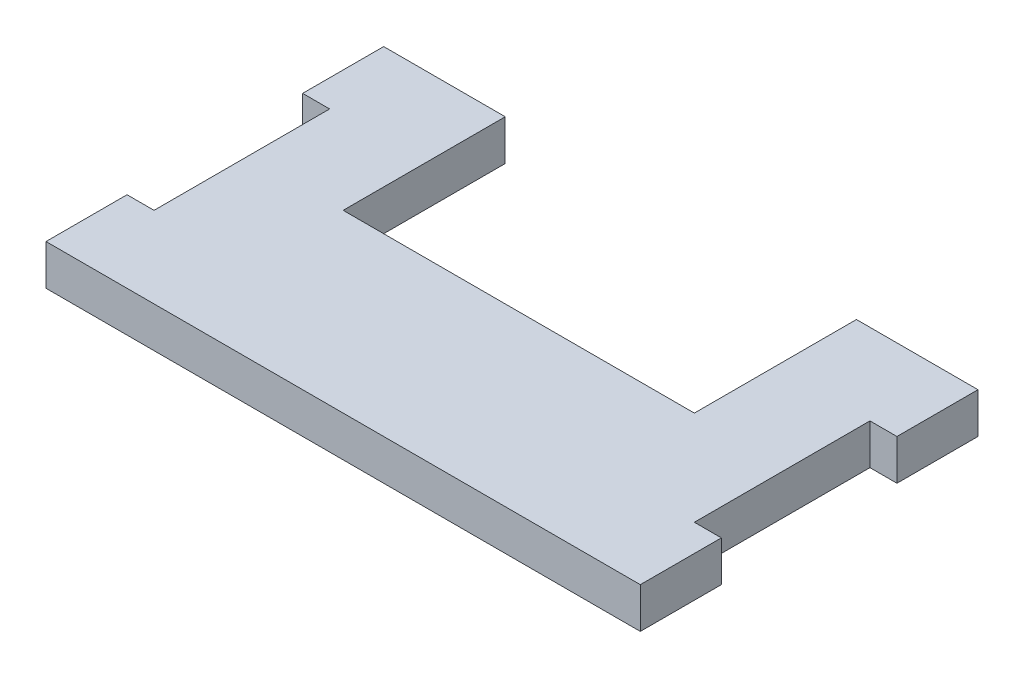
SolidWorks part; units mm, degrees
ref_plane "Front Plane" through (0, 0, 0) normal (0, 0, 1) x (1, 0, 0)
ref_plane "Top Plane" through (0, 0, 0) normal (0, 1, 0) x (1, 0, 0)
ref_plane "Right Plane" through (0, 0, 0) normal (1, 0, 0) x (0, 0, -1)
sketch "Sketch1" plane through (0, 0, 0) normal (0, 1, 0) x (1, 0, 0)
  line L0 (20, 25) -> (20, 0) construction
  line L1 (0, 0) -> (40, 0)
  line L2 (0, 0) -> (0, 25)
  line L3 (0, 25) -> (40, 25)
  line L4 (40, 0) -> (40, 25)
  line L5 (-2, 0) -> (-2, 6)
  line L6 (0, 12.5) -> (40, 12.5) construction
  line L7 (0, 25) -> (-2, 25)
  line L8 (0, 25) -> (0, 19)
  line L9 (0, 19) -> (-2, 19)
  line L10 (-2, 25) -> (-2, 19)
  line L11 (0, 6) -> (-2, 6)
  line L12 (0, 0) -> (0, 6)
  line L13 (0, 0) -> (-2, 0)
  line L14 (40, 0) -> (42, 0)
  line L15 (40, 25) -> (42, 25)
  line L16 (40, 19) -> (42, 19)
  line L17 (40, 6) -> (42, 6)
  line L18 (42, 25) -> (42, 19)
  line L19 (42, 0) -> (42, 6)
  line L20 (20, 13) -> (20, 25)
  line L21 (7, 25) -> (33, 25)
  line L22 (7, 25) -> (7, 13)
  line L23 (7, 13) -> (33, 13)
  line L24 (33, 25) -> (33, 13)
  dimension "D1" = 40
  dimension "D2" = 25
  dimension "D3" = 6
  dimension "D4" = 2
  dimension "D5" = 7
  dimension "D6" = 12
extrude "Boss-Extrude1" add sketch "Sketch1" along normal blind 3 contours L3 L24 L23 L22 L2 L1 L4 | L7 L10 L9 L2 | L13 L2 L11 L5 | L14 L19 L17 L4 | L18 L15 L4 L16
